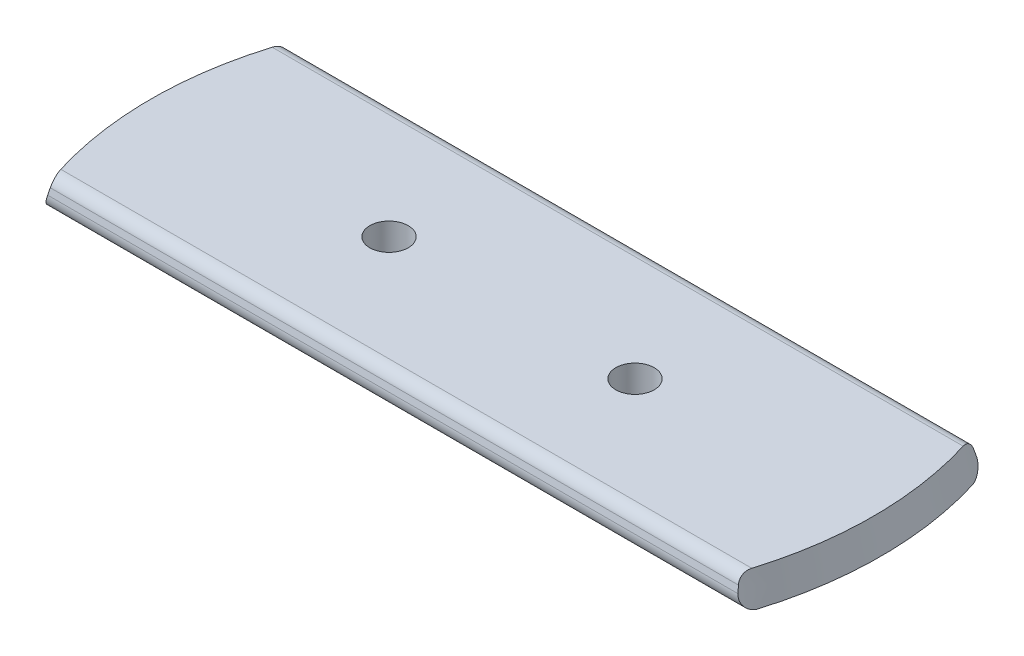
SolidWorks part; units mm, degrees
ref_plane "Front Plane" through (0, 0, 0) normal (0, 0, 1) x (1, 0, 0)
ref_plane "Top Plane" through (0, 0, 0) normal (0, 1, 0) x (1, 0, 0)
ref_plane "Right Plane" through (0, 0, 0) normal (1, 0, 0) x (0, 0, -1)
sketch "Sketch4" plane through (0, 0, 0) normal (0, 1, 0) x (1, 0, 0)
  line L0 (-7.1878, -2.54) -> (7.1878, -2.54)
  line L1 (-7.6234, -2.54) -> (-7.6234, 2.54) construction
  line L2 (7.6234, -2.54) -> (7.6234, 2.54) construction
  line L3 (-7.1878, 2.54) -> (7.1878, 2.54)
  line L4 (-7.6234, -2.54) -> (7.6234, 2.54) construction
  line L5 (7.6234, -2.54) -> (-7.6234, 2.54) construction
  line L6 (-7.6234, 0) -> (7.6234, 0) construction
  line L7 (0, 2.54) -> (0, -2.54) construction
  line L8 (-7.6234, 2.54) -> (7.6234, 2.54) construction
  line L9 (7.6234, -2.54) -> (-7.6234, -2.54) construction
  arc A0 (-7.1878, 2.54) -> (-7.1878, -2.54) centre (0, 0) ccw
  arc A1 (7.1878, 2.54) -> (-7.1878, 2.54) centre (0, 0) ccw construction
  arc A2 (-7.1878, -2.54) -> (7.1878, -2.54) centre (0, 0) ccw construction
  arc A3 (7.1878, -2.54) -> (7.1878, 2.54) centre (0, 0) ccw
  point P5 (0, 0)
  point P10 (2.54, 0)
  point P13 (-2.54, 0)
  dimension "D1" = 15.2468
  dimension "D2" = 5.08
  dimension "D3" = 2.54
sketch "Sketch1" plane through (0, 0, 0) normal (0, 1, 0) x (1, 0, 0)
  line L0 (-7.1842, -2.54) -> (7.1842, -2.54)
  line L1 (-7.62, -2.54) -> (-7.62, 2.54) construction
  line L2 (7.62, -2.54) -> (7.62, 2.54) construction
  line L3 (-7.1842, 2.54) -> (7.1842, 2.54)
  line L4 (-7.62, -2.54) -> (7.62, 2.54) construction
  line L5 (7.62, -2.54) -> (-7.62, 2.54) construction
  line L6 (-7.62, 0) -> (7.62, 0) construction
  line L7 (0, 2.54) -> (0, -2.54) construction
  line L8 (-7.62, 2.54) -> (7.62, 2.54) construction
  line L9 (7.62, -2.54) -> (-7.62, -2.54) construction
  arc A0 (-7.1842, 2.54) -> (-7.1842, -2.54) centre (0, 0) ccw
  arc A1 (7.1842, 2.54) -> (-7.1842, 2.54) centre (0, 0) ccw construction
  arc A2 (-7.1842, -2.54) -> (7.1842, -2.54) centre (0, 0) ccw construction
  arc A3 (7.1842, -2.54) -> (7.1842, 2.54) centre (0, 0) ccw
  point P5 (0, 0)
  point P10 (2.54, 0)
  point P13 (-2.54, 0)
  dimension "D1" = 15.24
  dimension "D2" = 5.08
  dimension "D3" = 2.54
extrude "Boss-Extrude1" add sketch "Sketch1" along normal blind 0.635 draft 14
hole_wizard "1/32 (0.03125) Diameter Hole1" positions "Sketch6" profile "Sketch5" hole size "1/32" standard "ANSI Inch"
sketch "Sketch6" plane through (0, 0, 0) normal (0, -1, 0) x (-1, 0, 0)
  point P0 (2.54, 0)
  point P3 (-2.54, 0)
sketch "Sketch5" plane through (-2.54, 0, 0) normal (1, 0, 0) x (0, 0, -1)
  line L0 (0, 0) -> (0, 12.9385)
  line L1 (0, 12.9385) -> (0.3969, 12.7)
  line L2 (0.3969, 12.7) -> (0.3969, 0)
  line L5 (0.3969, 0) -> (0, 0)
  line L10 (0, 12.9385) -> (-0.3969, 12.7) construction
  line L11 (0, -6.35) -> (0, 107.95) construction
  dimension "Hole Dia." = 0.7937
  dimension "Hole Depth" = 12.7
  dimension "Drill Angle" = 118
fillet "Fillet1" radius 0.254 4 edges at (0, 0, -2.54) (0, 0.635, -2.3817) (0, 0, 2.54) (0, 0.635, 2.3817)
